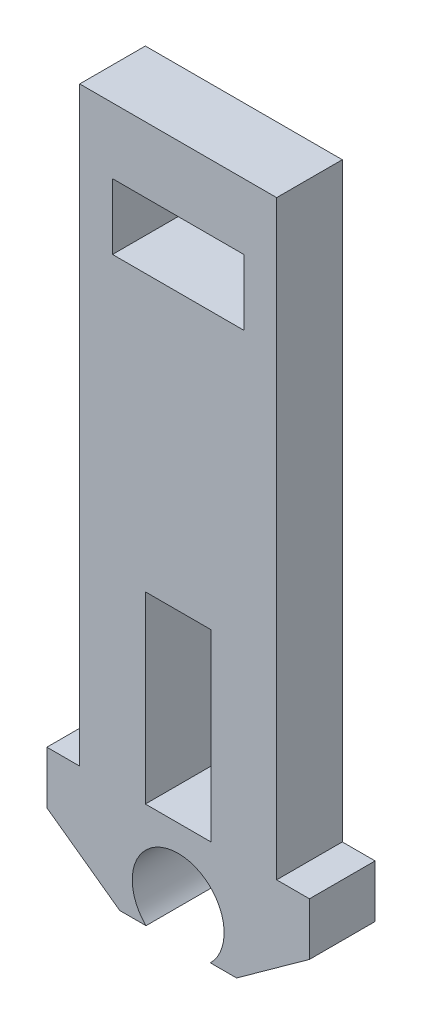
SolidWorks part; units mm, degrees
ref_plane "Спереди" through (0, 0, 0) normal (0, 0, 1) x (1, 0, 0)
ref_plane "Сверху" through (0, 0, 0) normal (0, 1, 0) x (1, 0, 0)
ref_plane "Справа" through (0, 0, 0) normal (1, 0, 0) x (0, 0, -1)
sketch "Sketch1" plane through (0, 0, 0) normal (0, 0, 1) x (1, 0, 0)
  line L0 (16.9495, 8) -> (19.4495, 8)
  line L1 (5, 0) -> (7, 0)
  line L2 (-0.5505, 4) -> (-0.5505, 8)
  line L3 (-0.5505, 8) -> (1.9495, 8)
  line L4 (19.4495, 4) -> (19.4495, 8)
  line L6 (1.9495, 8) -> (1.9495, 53)
  line L7 (1.9495, 53) -> (16.9495, 53)
  line L8 (16.9495, 8) -> (16.9495, 53)
  line L9 (5, 0) -> (-0.5505, 4)
  line L10 (13.899, 0) -> (19.4495, 4)
  line L11 (9.4495, 0) -> (9.4495, 8.4722) construction
  line L12 (11.899, 0) -> (13.899, 0)
  line L13 (6.9495, 8) -> (11.9495, 8)
  line L14 (4.4495, 48) -> (14.4495, 48)
  line L15 (4.4495, 48) -> (4.4495, 43)
  line L16 (4.4495, 43) -> (14.4495, 43)
  line L17 (14.4495, 48) -> (14.4495, 43)
  line L18 (11.9495, 8) -> (11.9495, 22)
  line L19 (11.9495, 22) -> (6.9495, 22)
  line L20 (6.9495, 22) -> (6.9495, 8)
  arc A0 (11.899, 0) -> (7, 0) centre (9.4495, 2.5) ccw
  point P15 (7, 0)
  point P16 (11.899, 0)
  point P22 (14.4495, 45.5)
  dimension "D6" = 7
  dimension "D1" = 5
  dimension "D2" = 5
  dimension "D3" = 45
  dimension "D4" = 15
  dimension "D5" = 2.5
  dimension "D7" = 2.5
  dimension "D8" = 2
  dimension "D9" = 2
  dimension "D10" = 10
  dimension "D11" = 2.5
  dimension "D12" = 5
  dimension "D13" = 5
  dimension "D14" = 14
extrude "Boss-Extrude1" add sketch "Sketch1" along normal blind 5
